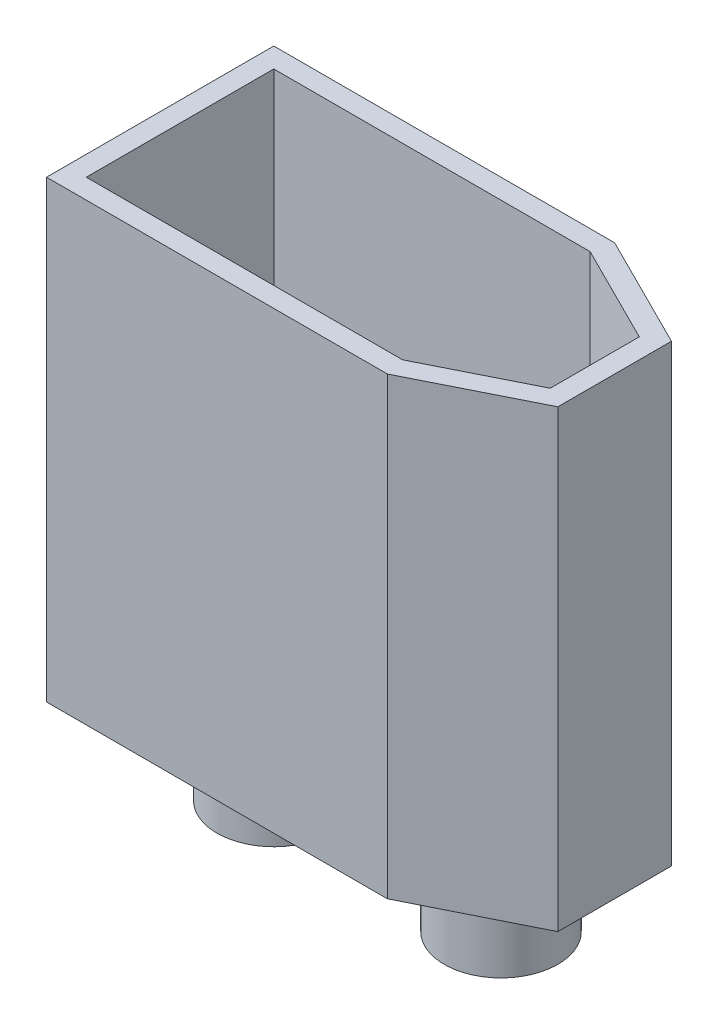
SolidWorks part; units mm, degrees
ref_plane "Alzado" through (0, 0, 0) normal (0, 0, 1) x (1, 0, 0)
ref_plane "Planta" through (0, 0, 0) normal (0, 1, 0) x (1, 0, 0)
ref_plane "Vista lateral" through (0, 0, 0) normal (1, 0, 0) x (0, 0, -1)
sketch "Croquis1" plane through (0, 0, 0) normal (0, 1, 0) x (1, 0, 0)
  line L0 (0, 0) -> (0, 8)
  line L1 (0, 8) -> (12, 8)
  line L2 (12, 8) -> (16, 6)
  line L3 (16, 6) -> (16, 2)
  line L4 (16, 2) -> (12, 0)
  line L5 (12, 0) -> (0, 0)
  dimension "D1" = 16
  dimension "D2" = 12
  dimension "D3" = 2
  dimension "D4" = 2
  dimension "D5" = 8
extrude "Saliente-Extruir1" add sketch "Croquis1" along normal blind 16 contours L5 L0 L1 L2 L3 L4
sketch "Croquis2" plane through (0, 16, 0) normal (0, 1, 0) x (1, 0, 0)
  line L0 (11.8348, 0.7) -> (15.3, 2.4326)
  line L1 (15.3, 2.4326) -> (15.3, 5.5674)
  line L2 (15.3, 5.5674) -> (11.8348, 7.3)
  line L3 (11.8348, 7.3) -> (0.7, 7.3)
  line L4 (0.7, 7.3) -> (0.7, 0.7)
  line L5 (0.7, 0.7) -> (11.8348, 0.7)
  line L6 (12, 0) -> (16, 2)
  line L7 (16, 2) -> (16, 6)
  line L8 (16, 6) -> (12, 8)
  line L9 (12, 8) -> (0, 8)
  line L10 (0, 8) -> (0, 0)
  line L11 (0, 0) -> (12, 0)
  line L12 (12, 0) -> (16, 2) construction
  line L13 (16, 2) -> (16, 6) construction
  line L14 (16, 6) -> (12, 8) construction
  line L15 (12, 8) -> (0, 8) construction
  line L16 (0, 8) -> (0, 0) construction
  line L17 (0, 0) -> (12, 0) construction
  dimension "D1" = 0
  dimension "D2" = 0.7
extrude "Cortar-Extruir1" cut sketch "Croquis2" against normal blind 15
sketch "Croquis3" plane through (0, 0, 0) normal (0, -1, 0) x (1, 0, 0)
  line L0 (0, -4) -> (16, -4) construction
  line L1 (0, 0) -> (0, -8) construction
  line L2 (16, -6) -> (16, -2) construction
  circle A0 centre (4, -4) radius 2
  circle A1 centre (12, -4) radius 2
  point P10 (6, -4)
  point P11 (2, -4)
  point P12 (10, -4)
  point P13 (14, -4)
  dimension "D1" = 4
  dimension "D2" = 6
  dimension "D3" = 6
extrude "Saliente-Extruir2" add sketch "Croquis3" along normal blind 3 separate body
